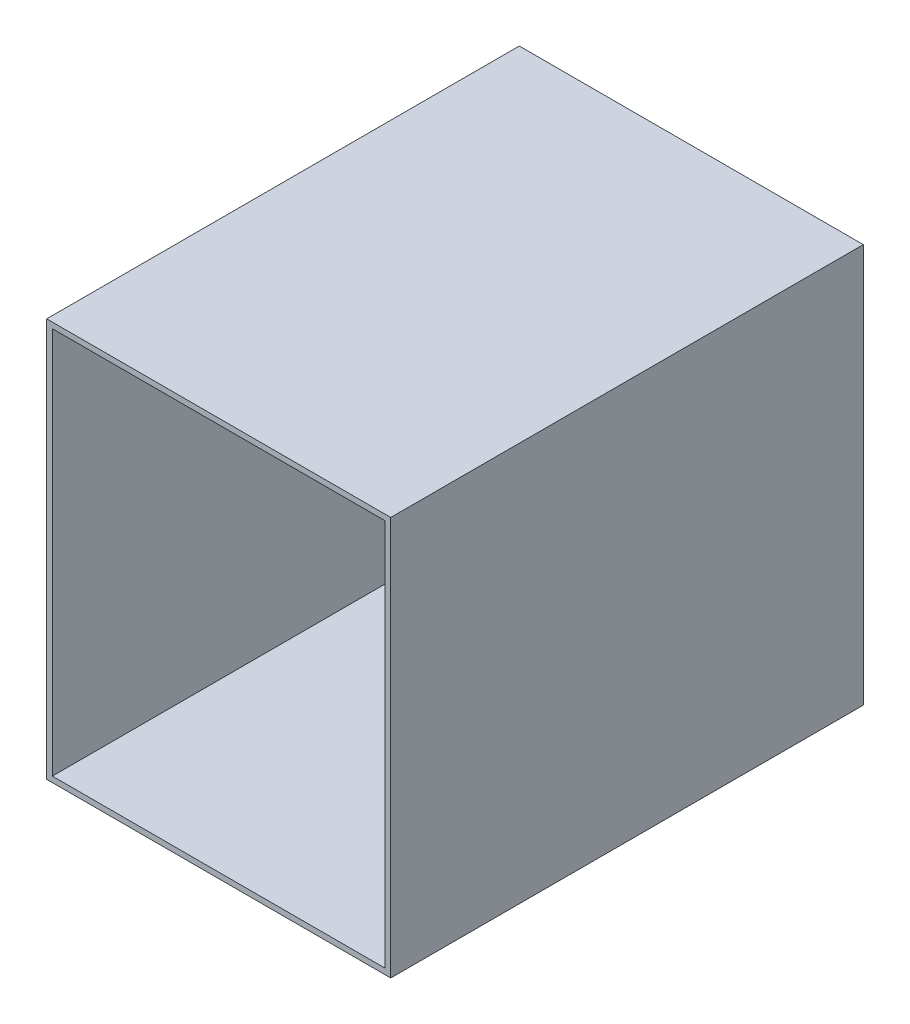
SolidWorks part; units mm, degrees
ref_plane "前视基准面" through (0, 0, 0) normal (0, 0, 1) x (1, 0, 0)
ref_plane "上视基准面" through (0, 0, 0) normal (0, 1, 0) x (1, 0, 0)
ref_plane "右视基准面" through (0, 0, 0) normal (1, 0, 0) x (0, 0, -1)
other "Configuration Table"
sketch "草图1" plane through (0, 0, 0) normal (0, 0, 1) x (1, 0, 0)
  line L0 (0, 0) -> (182, 0)
  line L1 (182, 0) -> (182, 211)
  line L2 (182, 211) -> (0, 211)
  line L3 (0, 211) -> (0, 0)
  dimension "width" = 182
  dimension "height" = 211
extrude "BlockExtrude" add sketch "草图1" along normal blind 250
shell "抽壳1" thickness 3
